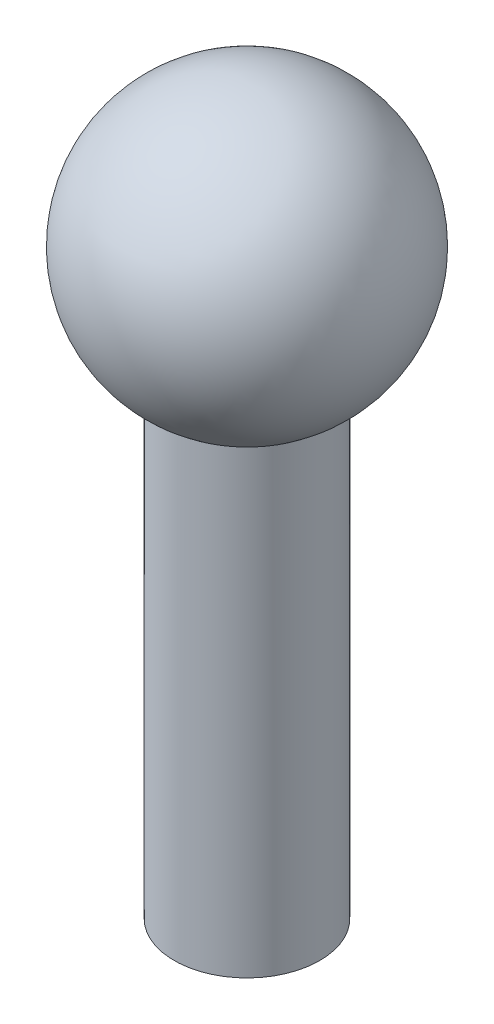
SolidWorks part; units mm, degrees
ref_plane "Front Plane" through (0, 0, 0) normal (0, 0, 1) x (1, 0, 0)
ref_plane "Top Plane" through (0, 0, 0) normal (0, 1, 0) x (1, 0, 0)
ref_plane "Right Plane" through (0, 0, 0) normal (1, 0, 0) x (0, 0, -1)
sketch "Sketch1" plane through (0, 0, 0) normal (0, 0, 1) x (1, 0, 0)
  line L0 (0, 0) -> (0, 16) construction
  line L1 (0, 0) -> (-2, 0)
  line L2 (-2, 0) -> (-2, 12.6519)
  line L3 (0, 19.9) -> (0, 0)
  circle A0 centre (0, 16) radius 3.9
  dimension "D2" = 7.8
  dimension "D1" = 16
  dimension "D3" = 2
revolve "Revolve1" add sketch "Sketch1" angle 360 about L0
